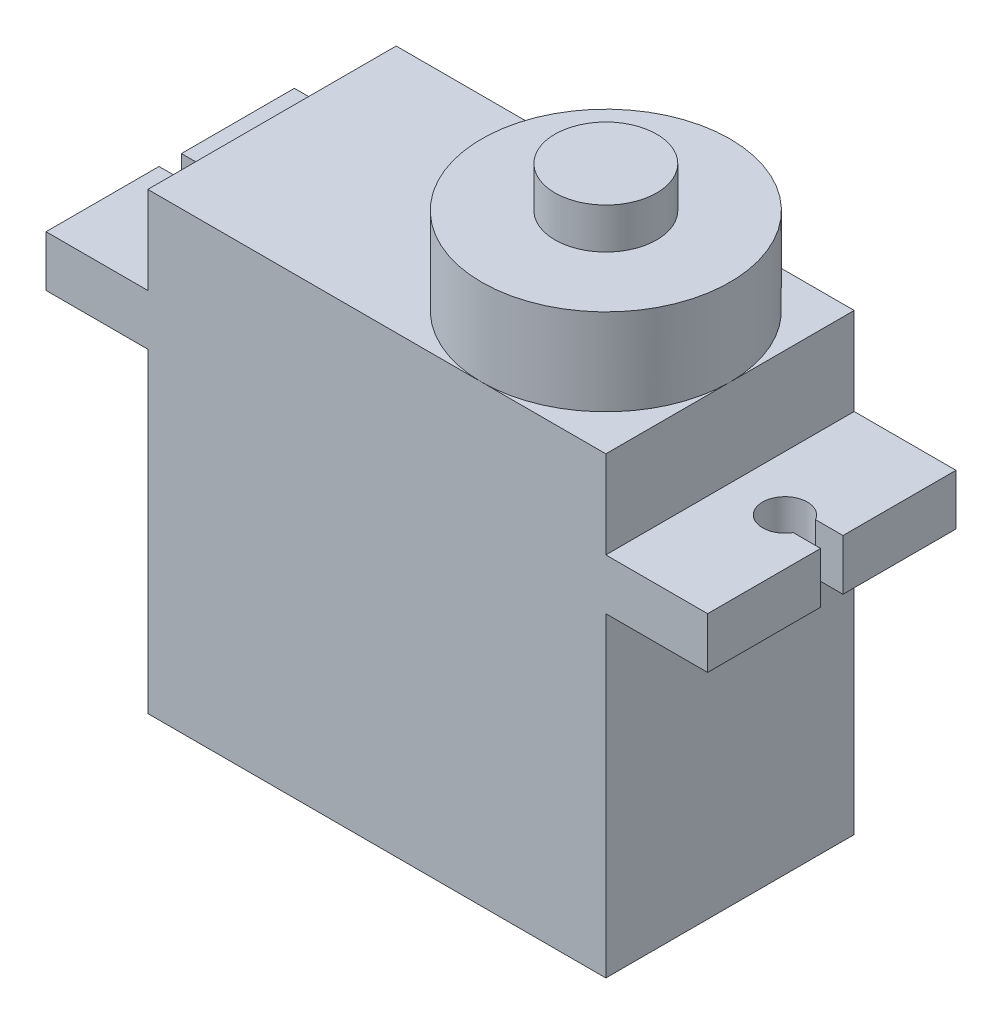
SolidWorks part; units mm, degrees
ref_plane "Front Plane" through (0, 0, 0) normal (0, 0, 1) x (1, 0, 0)
ref_plane "Top Plane" through (0, 0, 0) normal (0, 1, 0) x (1, 0, 0)
ref_plane "Right Plane" through (0, 0, 0) normal (1, 0, 0) x (0, 0, -1)
sketch "Sketch1" plane through (0, 0, 0) normal (0, 1, 0) x (1, 0, 0)
  line L1 (-7.881, 5.1051) -> (14.619, 5.1051)
  line L2 (-7.881, 5.1051) -> (-7.881, -7.0949)
  line L3 (-7.881, -7.0949) -> (14.619, -7.0949)
  line L4 (14.619, 5.1051) -> (14.619, -7.0949)
  dimension "D1" = 22.5
  dimension "D2" = 12.2
extrude "Boss-Extrude1" add sketch "Sketch1" along normal blind 22.3
sketch "Sketch2" plane through (14.619, 0, 0) normal (1, 0, 0) x (0, 0, -1)
  line L0 (-7.0949, 22.3) -> (-7.0949, 0) construction
  line L1 (5.1051, 22.3) -> (5.1051, 0) construction
  line L2 (-7.0949, 18) -> (5.1051, 18)
  line L3 (-7.0949, 18) -> (-7.0949, 15.5)
  line L4 (-7.0949, 15.5) -> (5.1051, 15.5)
  line L5 (5.1051, 18) -> (5.1051, 15.5)
  line L6 (-7.0949, 22.3) -> (5.1051, 22.3) construction
  dimension "D1" = 4.3
  dimension "D2" = 2.5
extrude "Boss-Extrude2" add sketch "Sketch2" along normal blind 5
sketch "Sketch3" plane through (0, 18, 0) normal (0, 1, 0) x (1, 0, 0)
  line L0 (19.619, 5.1051) -> (14.619, 5.1051) construction
  line L1 (19.619, 5.1051) -> (19.619, -7.0949) construction
  line L2 (18.2717, -0.4449) -> (19.619, -0.4449)
  line L3 (18.2717, -1.5449) -> (19.619, -1.5449)
  line L4 (19.619, -7.0949) -> (14.619, -7.0949) construction
  line L5 (19.619, -0.4449) -> (19.619, -1.5449)
  arc A0 (18.2717, -0.4449) -> (18.2717, -1.5449) centre (17.319, -0.9949) ccw
  point P10 (18.9454, -0.4449)
  dimension "D3" = 2.2
  dimension "D1" = 6.1
  dimension "D2" = 2.3
  dimension "D4" = 1.1
  dimension "D5" = 5.55
extrude "Cut-Extrude1" cut sketch "Sketch3" against normal through all contours L5 L3 A0 L2
sketch "Sketch4" plane through (0, 0, 7.0949) normal (0, 0, 1) x (1, 0, 0)
  line L0 (3.369, 0) -> (3.369, 22.3) construction
  line L1 (-7.881, 0) -> (14.619, 0) construction
  line L2 (-7.881, 22.3) -> (14.619, 22.3) construction
  point P4 (-1.431, 21.7203)
  point P5 (0, 0)
  point P6 (0, 0)
  point P7 (-1.431, 22.3)
ref_plane "Plane1" through (3.369, 0, 0) normal (1, 0, 0) x (0, 0, -1)
mirror "Mirror1" about plane through (3.369, 0, 0) normal (1, 0, 0) of "Cut-Extrude1", "Boss-Extrude2"
sketch "Sketch5" plane through (0, 22.3, 0) normal (0, 1, 0) x (1, 0, 0)
  line L0 (14.619, 5.1051) -> (-7.881, 5.1051) construction
  line L1 (14.619, -7.0949) -> (14.619, 5.1051) construction
  circle A0 centre (8.519, -0.9949) radius 6.1
  dimension "D1" = 12.2
  dimension "D2" = 6.1
  dimension "D3" = 6.1
extrude "Boss-Extrude3" add sketch "Sketch5" along normal blind 4.25
sketch "Sketch6" plane through (0, 26.55, 0) normal (0, 1, 0) x (1, 0, 0)
  circle A0 centre (8.519, -0.9949) radius 2.5
  dimension "D1" = 5
extrude "Boss-Extrude4" add sketch "Sketch6" along normal blind 2 contours A0
